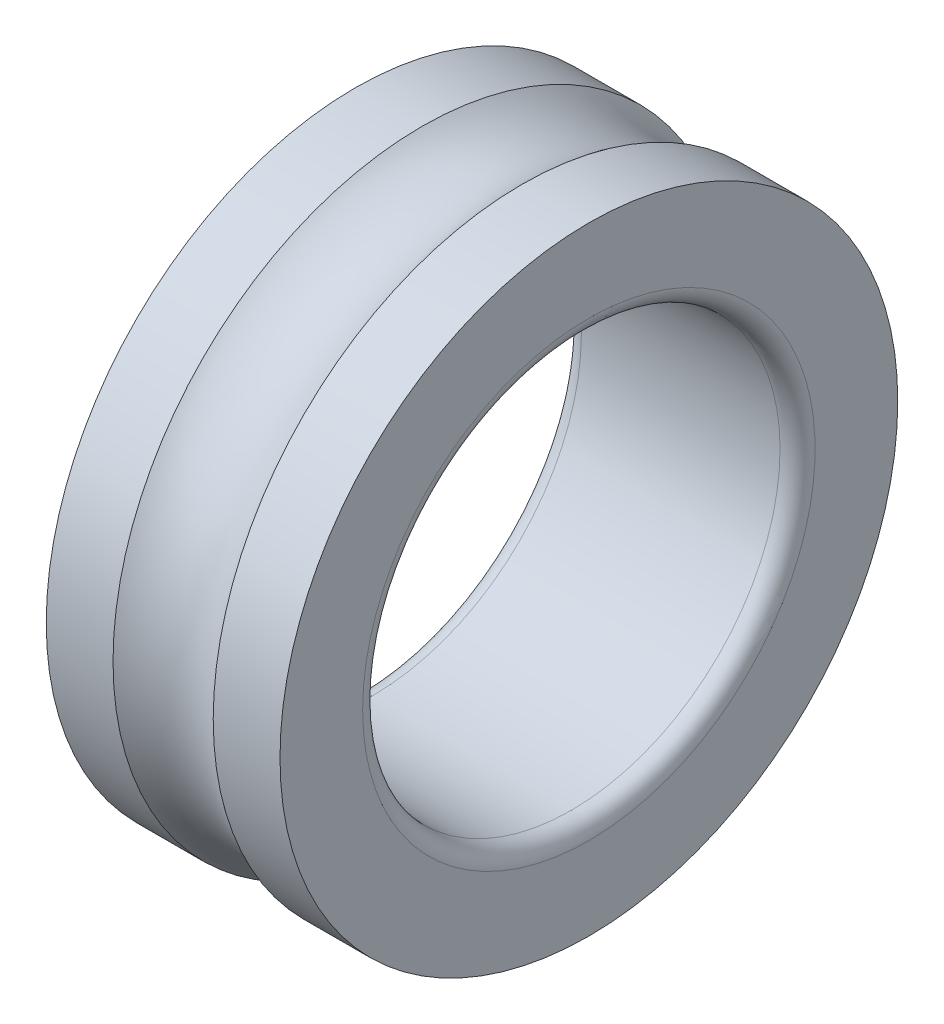
SolidWorks part; units mm, degrees
material "AISI 316 Stainless Steel Sheet (SS)"
ref_plane "Front Plane" through (0, 0, 0) normal (0, 0, 1) x (1, 0, 0)
ref_plane "Top Plane" through (0, 0, 0) normal (0, 1, 0) x (1, 0, 0)
ref_plane "Right Plane" through (0, 0, 0) normal (1, 0, 0) x (0, 0, -1)
sketch "Sketch1" plane through (0, 0, 0) normal (0, 0, 1) x (1, 0, 0)
  line L0 (-28.3637, 0) -> (23.9344, 0) construction
  line L1 (0, 0) -> (0, 25) construction
  line L2 (-14, 37) -> (-6, 37)
  line L3 (-14, 37) -> (-14, 27.1)
  line L4 (-11.9, 25) -> (11.9, 25)
  line L5 (14, 37) -> (14, 27.1)
  line L6 (-14, 37) -> (14, 25) construction
  line L7 (-14, 25) -> (14, 37) construction
  line L8 (6, 37) -> (14, 37)
  arc A0 (6, 37) -> (-6, 37) centre (0, 45) cw
  arc A1 (11.9, 25) -> (14, 27.1) centre (11.9, 27.1) ccw
  arc A2 (-14, 27.1) -> (-11.9, 25) centre (-11.9, 27.1) ccw
  point P3 (0, 31)
  dimension "D5" = 10
  dimension "D6" = 2.1
  dimension "D1" = 28
  dimension "D2" = 25
  dimension "D3" = 37
  dimension "D4" = 8
revolve "Revolve1" add sketch "Sketch1" angle 360 about L0
